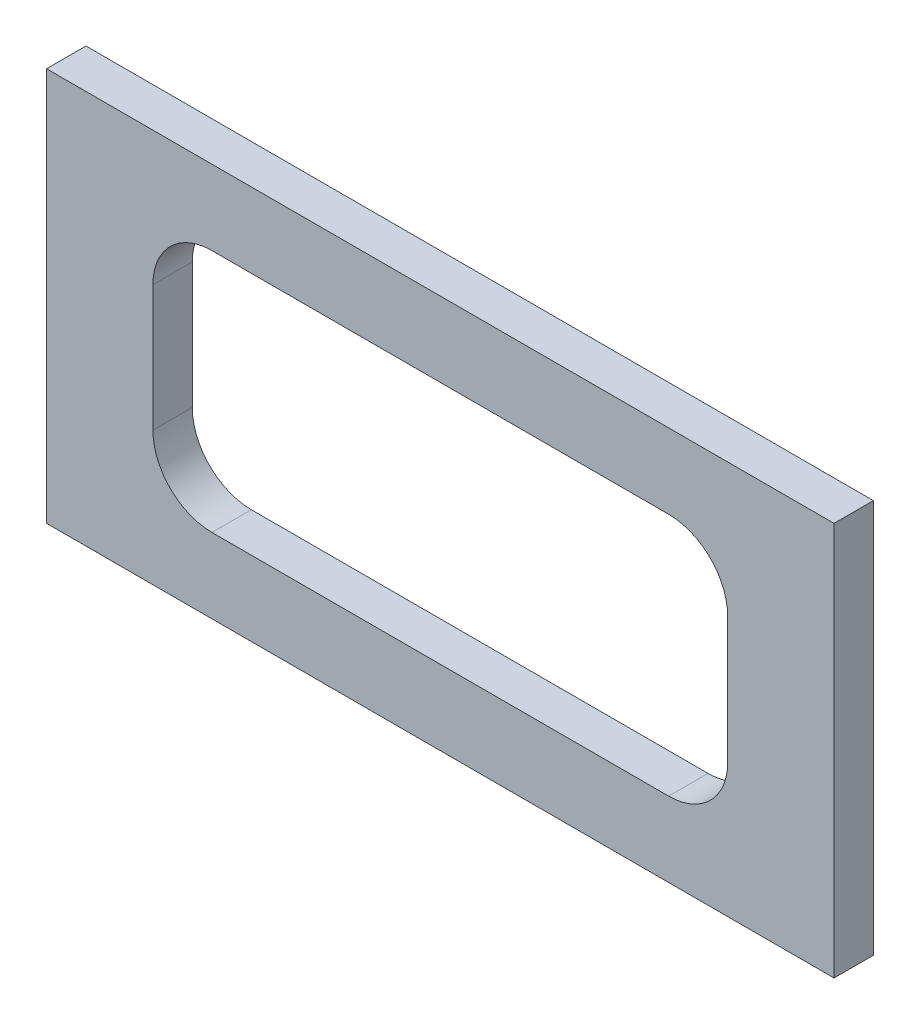
SolidWorks part; units mm, degrees
material "PVC 0.007 Plasticized"
ref_plane "Front Plane" through (0, 0, 0) normal (0, 0, 1) x (1, 0, 0)
ref_plane "Top Plane" through (0, 0, 0) normal (0, 1, 0) x (1, 0, 0)
ref_plane "Right Plane" through (0, 0, 0) normal (1, 0, 0) x (0, 0, -1)
sketch "Sketch1" plane through (0, 0, 0) normal (0, 0, 1) x (1, 0, 0)
  line L1 (0, 0) -> (100, 0)
  line L2 (0, 0) -> (0, 50)
  line L3 (0, 50) -> (100, 50)
  line L4 (100, 0) -> (100, 50)
  dimension "D1" = 100
  dimension "D2" = 50
extrude "Boss-Extrude1" add sketch "Sketch1" along normal blind 5
sketch "Sketch2" plane through (0, 0, 5) normal (0, 0, 1) x (1, 0, 0)
  line L0 (0, 50) -> (0, 0) construction
  line L1 (21, 40.5) -> (79, 40.5)
  line L2 (13.5, 33) -> (13.5, 17)
  line L3 (21, 9.5) -> (79, 9.5)
  line L4 (86.5, 33) -> (86.5, 17)
  line L5 (100, 50) -> (0, 50) construction
  arc A0 (21, 40.5) -> (13.5, 33) centre (21, 33) ccw
  arc A1 (13.5, 17) -> (21, 9.5) centre (21, 17) ccw
  arc A2 (86.5, 33) -> (79, 40.5) centre (79, 33) ccw
  arc A3 (79, 9.5) -> (86.5, 17) centre (79, 17) ccw
  dimension "D5" = 15
  dimension "D6" = 15
  dimension "D7" = 15
  dimension "D8" = 15
  dimension "D9" = 7.5
  dimension "D10" = 7.5
  dimension "D11" = 7.5
  dimension "D12" = 7.5
  dimension "D13" = 7.5
  dimension "D14" = 7.5
  dimension "D15" = 7.5
  dimension "D16" = 7.5
  dimension "D3" = 13.5
  dimension "D4" = 9.5
extrude "Cut-Extrude1" cut sketch "Sketch2" against normal blind 5
